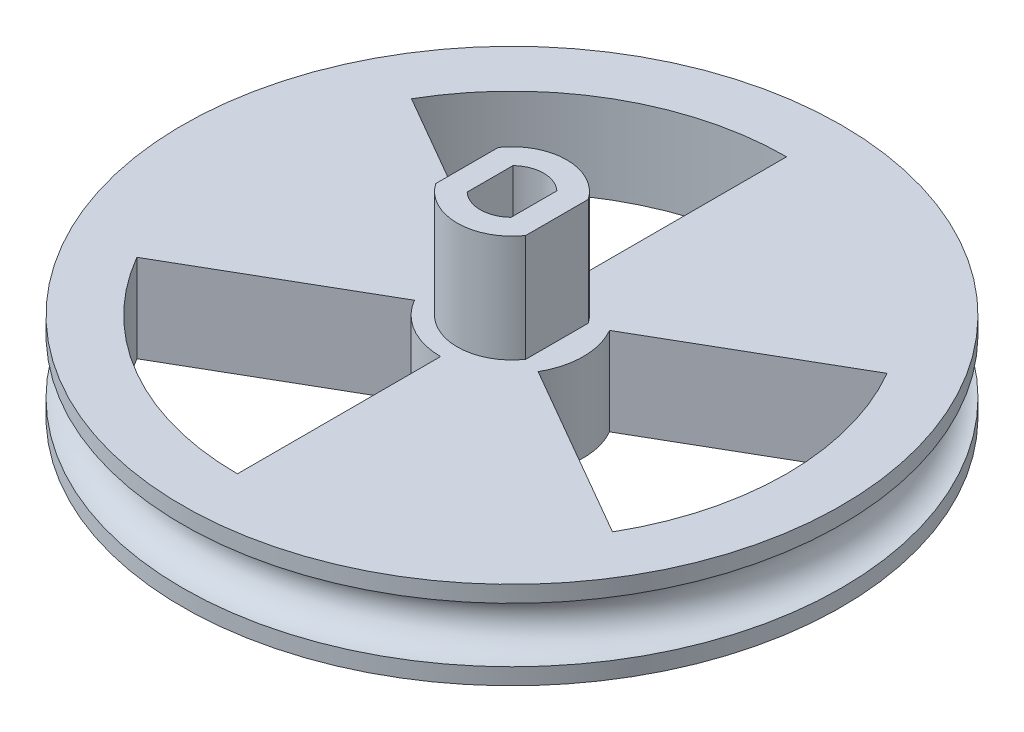
SolidWorks part; units mm, degrees
ref_plane "Plano frontal" through (0, 0, 0) normal (0, 0, 1) x (1, 0, 0)
ref_plane "Plano superior" through (0, 0, 0) normal (0, 1, 0) x (1, 0, 0)
ref_plane "Plano direito" through (0, 0, 0) normal (1, 0, 0) x (0, 0, -1)
sketch "Esboço1" plane through (0, 0, 0) normal (0, 1, 0) x (1, 0, 0)
  line L0 (0, 0) -> (-4.75, 0)
  line L1 (-4.75, 0) -> (4.75, 0)
  line L2 (4.75, 0) -> (0, 0)
  line L3 (-3.9, 0) -> (0, 0)
  line L4 (3.9, 0) -> (0, 0)
  line L5 (-3.9, 0) -> (-3.9, 2.7115)
  line L6 (-3.9, 2.7115) -> (-3.9, -2.7115)
  line L7 (3.9, 2.7115) -> (3.9, -2.7115)
  line L8 (3.9, -2.7115) -> (3.9, 2.7115)
  circle A0 centre (0, 0) radius 4.75
  dimension "D1" = 9.5
  dimension "D2" = 3.9
  dimension "D3" = 3.9
extrude "Extrusão1" add sketch "Esboço1" along normal blind 9.3 contours L6 A0 L7 L1 L0 | L7 A0 L5 L0 L1
sketch "Esboço2" plane through (0, 9.3, 0) normal (0, 1, 0) x (1, 0, 0)
  line L0 (0, 0) -> (-2.75, 0)
  line L1 (-2.75, 0) -> (2.75, 0)
  line L2 (2.75, 0) -> (0, 0)
  line L3 (-1.9, 0) -> (0, 0)
  line L4 (1.9, 0) -> (0, 0)
  line L5 (-1.9, 0) -> (-1.9, 1.9881)
  line L6 (-1.9, 1.9881) -> (-1.9, -1.9881)
  line L7 (-1.9, -1.9881) -> (-1.9, 0)
  line L8 (1.9, 0) -> (1.9, -1.9881)
  line L9 (1.9, -1.9881) -> (1.9, 1.9881)
  line L10 (1.9, 1.9881) -> (1.9, 0)
  circle A0 centre (0, 0) radius 2.75
  dimension "D1" = 5.5
  dimension "D2" = 1.9
  dimension "D3" = 1.9
extrude "Extrusão2" cut sketch "Esboço2" against normal blind 7.3 contours L9 A0 L5 L0 L1 | L6 A0 L8 L1 L0
scale "Escala3" bodies to scale 102 scale about origin uniform scaling yes scale factor 1.05
sketch "Esboço3" plane through (0, 0, 0) normal (0, -1, 0) x (1, 0, 0)
  circle A0 centre (0, 0) radius 30
extrude "Extrusão3" add sketch "Esboço3" along normal blind 8
sketch "Esboço4" plane through (0, 0, 0) normal (1, 0, 0) x (0, 0, -1)
  line L2 (30, 0) -> (-30, 0) construction
  circle A0 centre (-30, -4) radius 2.5
  dimension "D1" = 4
  dimension "D2" = 5
ref_plane "Plano1" through (0, -4, 0) normal (0, 1, 0) x (-1, 0, 0)
sketch "Esboço6" plane through (0, -4, 0) normal (0, 1, 0) x (-1, 0, 0)
  circle A0 centre (0, 0) radius 30
sweep "Varredura de corte1" cut profiles "Esboço4" path "Esboço6"
sketch "Esboço7" plane through (0, -8, 0) normal (0, -1, 0) x (1, 0, 0)
  line L0 (-21.6506, 12.5) -> (-5.6292, 3.25)
  line L7 (0, 6.5) -> (0, 25)
  line L8 (0, -25) -> (0, -6.5)
  line L9 (-21.6506, -12.5) -> (-5.6292, -3.25)
  line L10 (21.6506, 12.5) -> (5.6292, 3.25)
  line L11 (21.6506, -12.5) -> (5.6292, -3.25)
  arc A0 (21.6506, -12.5) -> (21.6506, 12.5) centre (0, 0) ccw
  arc A1 (-5.6292, -3.25) -> (0, -6.5) centre (0, 0) ccw
  arc A2 (-21.6506, -12.5) -> (0, -25) centre (0, 0) ccw
  arc A3 (0, 6.5) -> (-5.6292, 3.25) centre (0, 0) ccw
  arc A4 (5.6292, -3.25) -> (5.6292, 3.25) centre (0, 0) ccw
  arc A5 (0, 25) -> (-21.6506, 12.5) centre (0, 0) ccw
  dimension "D1" = 13
extrude "Extrusão6" cut sketch "Esboço7" against normal blind 8
